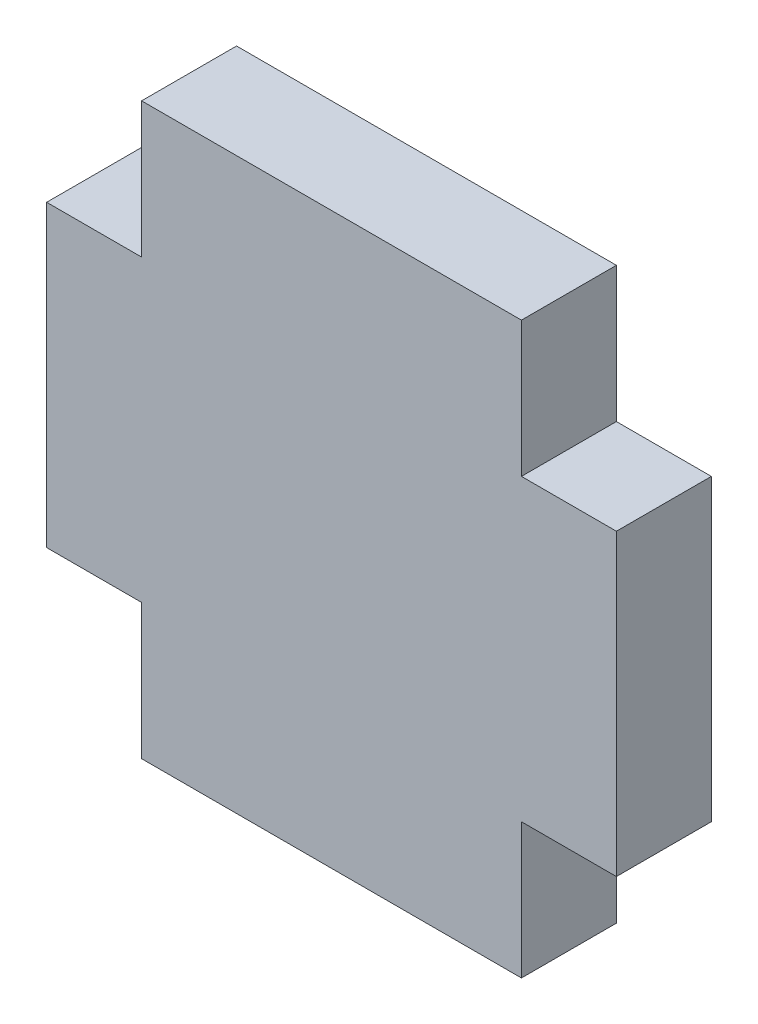
SolidWorks part; units mm, degrees
material "ABS"
ref_plane "Plan de face" through (0, 0, 0) normal (0, 0, 1) x (1, 0, 0)
ref_plane "Plan de dessus" through (0, 0, 0) normal (0, 1, 0) x (1, 0, 0)
ref_plane "Plan de droite" through (0, 0, 0) normal (1, 0, 0) x (0, 0, -1)
sketch "Esquisse1" plane through (0, 0, 0) normal (0, 0, 1) x (1, 0, 0)
  line L1 (-12.7, 19.05) -> (12.7, 19.05)
  line L2 (-12.7, 19.05) -> (-12.7, -19.05)
  line L3 (-12.7, -19.05) -> (12.7, -19.05)
  line L4 (12.7, 19.05) -> (12.7, -19.05)
  line L5 (-19.05, 10) -> (19.05, 10)
  line L6 (-19.05, 10) -> (-19.05, -10)
  line L7 (-19.05, -10) -> (19.05, -10)
  line L8 (19.05, 10) -> (19.05, -10)
  point P8 (0, 10)
  point P11 (-19.05, 0)
  point P12 (0, 19.05)
  point P13 (-12.7, 0)
  dimension "D1" = 25.4
  dimension "D2" = 6.35
  dimension "D3" = 20
  dimension "D4" = 38.1
extrude "Boss.-Extru.1" add sketch "Esquisse1" along normal blind 6.35 contours L2 L7 L4 L5 | L6 L7 L2 L5 | L7 L2 L3 L4 | L8 L5 L4 L7 | L2 L5 L4 L1
